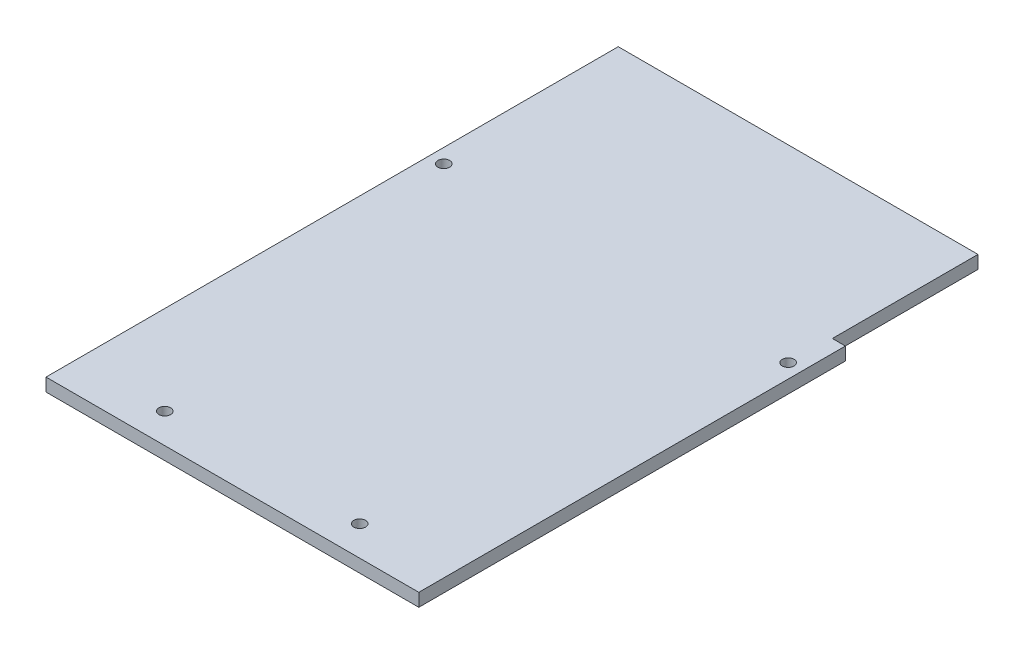
SolidWorks part; units mm, degrees
material "Acrylic (Medium-high impact)"
ref_plane "Front Plane" through (0, 0, 0) normal (0, 0, 1) x (1, 0, 0)
ref_plane "Top Plane" through (0, 0, 0) normal (0, 1, 0) x (1, 0, 0)
ref_plane "Right Plane" through (0, 0, 0) normal (1, 0, 0) x (0, 0, -1)
sketch "Sketch1" plane through (0, 0, 0) normal (0, 1, 0) x (1, 0, 0)
  line L1 (-22.7879, -83.4622) -> (113.7371, -83.4622)
  line L2 (-22.7879, -83.4622) -> (-22.7879, 126.0878)
  line L3 (-22.7879, 126.0878) -> (113.7371, 126.0878)
  line L4 (113.7371, -83.4622) -> (113.7371, 126.0878)
  dimension "D1" = 209.55
  dimension "D2" = 136.525
extrude "Boss-Extrude1" add sketch "Sketch1" along normal blind 4.7625
sketch "Sketch2" plane through (0, 4.7625, 0) normal (0, 1, 0) x (1, 0, 0)
  line L1 (113.7371, 126.0878) -> (108.9619, 126.0878)
  line L2 (113.7371, 126.0878) -> (113.7371, 72.7478)
  line L3 (113.7371, 72.7478) -> (108.9619, 72.7478)
  line L4 (108.9619, 126.0878) -> (108.9619, 72.7478)
  dimension "D1" = 4.7752
  dimension "D2" = 53.34
extrude "Cut-Extrude1" cut sketch "Sketch2" against normal through all
hole_wizard "#8 Clearance Hole1" positions "Sketch3" profile "Sketch4" hole size "#8" standard "ANSI Inch" end condition through all
sketch "Sketch3" plane through (0, 4.7625, 0) normal (0, 1, 0) x (1, 0, 0)
  point P0 (81.1616, -72.5402)
  point P2 (9.7876, -72.5402)
  point P3 (-17.5809, 56.9998)
  point P6 (108.5301, 56.9998)
sketch "Sketch4" plane through (81.1616, 4.7625, 72.5402) normal (1, 0, 0) x (0, 0, 1)
  line L0 (0, 0) -> (0, 4.7625)
  line L1 (0, 4.7625) -> (2.1526, 4.7625)
  line L2 (2.1526, 4.7625) -> (2.1526, 0)
  line L5 (2.1526, 0) -> (0, 0)
  line L11 (0, -6.35) -> (0, 107.95) construction
  dimension "Thru Hole Dia." = 4.3053
  dimension "Thru Hole Depth" = 4.7625
